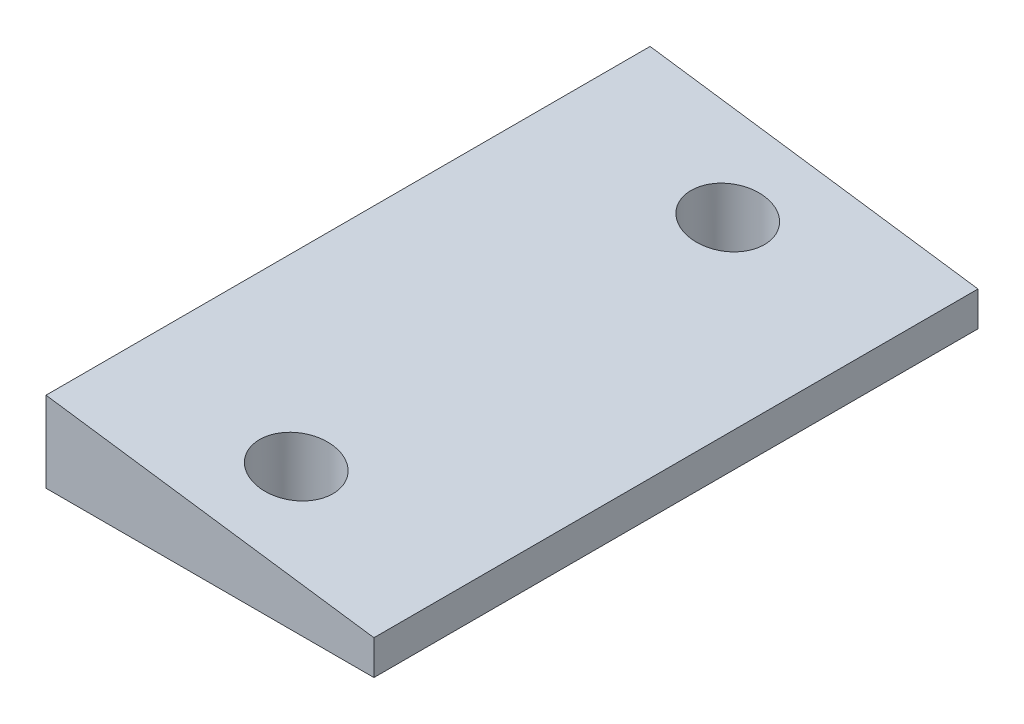
SolidWorks part; units mm, degrees
ref_plane "Płaszczyzna przednia" through (0, 0, 0) normal (0, 0, 1) x (1, 0, 0)
ref_plane "Płaszczyzna górna" through (0, 0, 0) normal (0, 1, 0) x (1, 0, 0)
ref_plane "Płaszczyzna prawa" through (0, 0, 0) normal (1, 0, 0) x (0, 0, -1)
sketch "Szkic1" plane through (0, 0, 0) normal (0, 0, 1) x (1, 0, 0)
  line L0 (-29.0173, 0) -> (30.2457, 0) construction
  line L1 (0, 20.0247) -> (0, -27.335) construction
  line L2 (-16.5582, 5.2371) -> (-16.5582, -4.1034)
  line L3 (-16.5582, -4.1034) -> (21.4418, -4.1034)
  line L4 (21.4418, -4.1034) -> (21.4418, -0.1034)
  line L6 (-16.5582, -28.29) -> (-16.5582, 30.6374) construction
  line L7 (-19.4953, -15.6612) -> (-14.6544, 18.7831) construction
  line L8 (-16.5582, 5.2371) -> (21.4418, -0.1034)
  point P14 (0, 0)
  point P15 (0, 0)
  point P16 (0, 0)
  point P17 (-16.5582, 9.3035)
  point P18 (0, 0)
  point P19 (0, 0)
  point P20 (0, 0)
  point P21 (-16.5582, -25.2338)
  point P22 (-16.5582, 30.6374)
  point P23 (-16.5582, -28.29)
  point P24 (0, -27.335)
  dimension "D1" = 38
  dimension "D2" = 8
  dimension "D3" = 4
extrude "Dodanie-wyciągnięcie1" add sketch "Szkic1" along normal blind 70
ref_plane "Płaszczyzna1" through (0, 5.2371, 0) normal (0, -1, 0) x (-1, 0, 0)
sketch "Szkic2" plane through (0, 5.2371, 0) normal (0, -1, 0) x (-1, 0, 0)
  line L0 (-2.4418, -71.2527) -> (-2.4418, 2.237) construction
  line L1 (21.508, -35) -> (-18.9278, -35) construction
  circle A0 centre (-2.4418, -60) radius 4.25
  circle A1 centre (-2.4418, -10) radius 4.25
  point P8 (0, 0)
  point P9 (0, 0)
  dimension "D1" = 8.5
  dimension "D2" = 25
  dimension "D3" = 8.5
  dimension "D4" = 25
extrude "Wytnij-wyciągnięcie1" cut sketch "Szkic2" along normal blind 10
